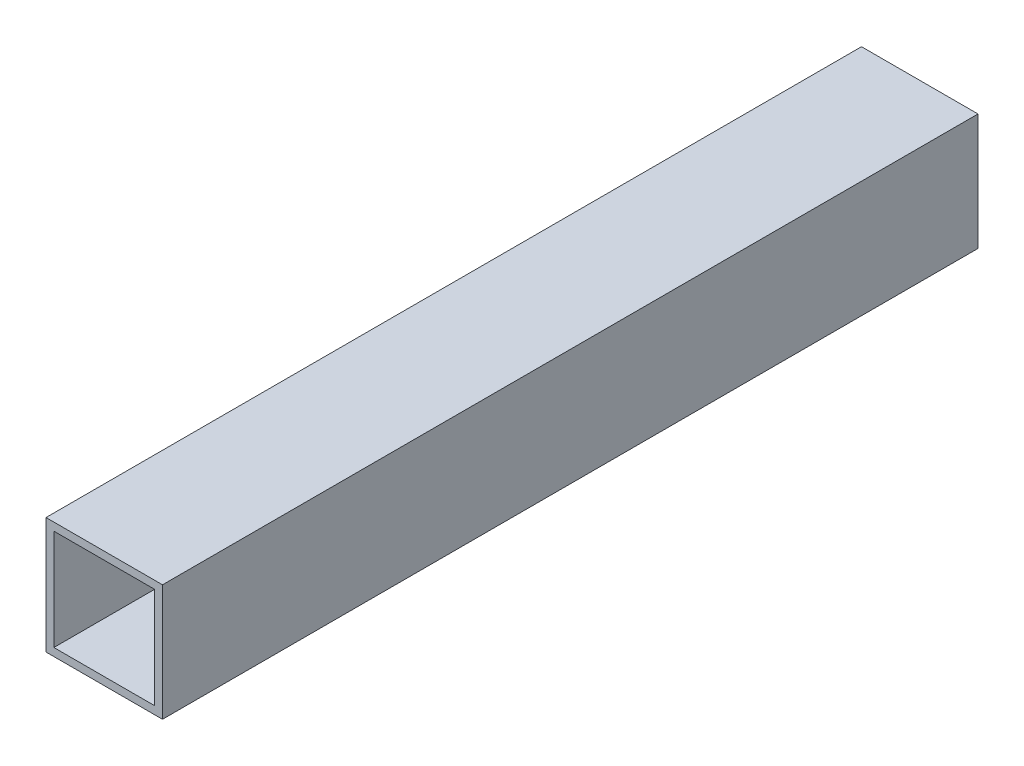
SolidWorks part; units mm, degrees
material "6063-O, Extruded Rod (SS)"
ref_plane "Front Plane" through (0, 0, 0) normal (0, 0, 1) x (1, 0, 0)
ref_plane "Top Plane" through (0, 0, 0) normal (0, 1, 0) x (1, 0, 0)
ref_plane "Right Plane" through (0, 0, 0) normal (1, 0, 0) x (0, 0, -1)
sketch "Sketch1" plane through (0, 0, 0) normal (0, 0, 1) x (1, 0, 0)
  line L0 (-10.9855, 10.9855) -> (10.9855, 10.9855)
  line L1 (-12.7, -12.7) -> (12.7, -12.7)
  line L2 (-12.7, -12.7) -> (-12.7, 12.7)
  line L3 (-12.7, 12.7) -> (12.7, 12.7)
  line L4 (12.7, -12.7) -> (12.7, 12.7)
  line L5 (-12.7, -12.7) -> (12.7, 12.7) construction
  line L6 (-12.7, 12.7) -> (12.7, -12.7) construction
  line L7 (10.9855, -10.9855) -> (10.9855, 10.9855)
  line L8 (-10.9855, -10.9855) -> (10.9855, -10.9855)
  line L9 (-10.9855, -10.9855) -> (-10.9855, 10.9855)
  point P0 (0, 0)
  dimension "D1" = 25.4
  dimension "D2" = 25.4
  dimension "D3" = 1.7145
extrude "Boss-Extrude1" add sketch "Sketch1" along normal mid plane 177.8
